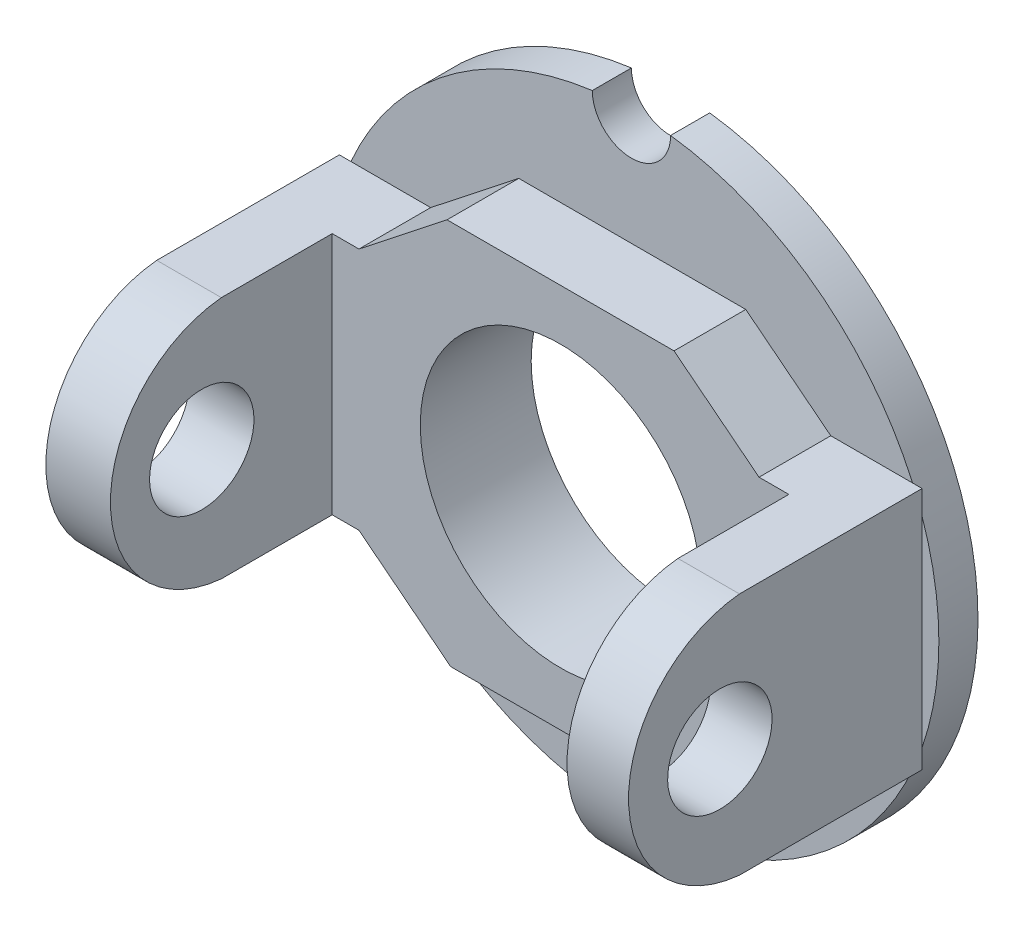
SolidWorks part; units mm, degrees
ref_plane "Plan de face" through (0, 0, 0) normal (0, 0, 1) x (1, 0, 0)
ref_plane "Plan de dessus" through (0, 0, 0) normal (0, 1, 0) x (1, 0, 0)
ref_plane "Plan de droite" through (0, 0, 0) normal (1, 0, 0) x (0, 0, -1)
sketch "Sketch1" plane through (0, 0, 0) normal (0, 0, 1) x (1, 0, 0)
  circle A0 centre (0, 0) radius 10.75
  arc A1 (2.9335, 23.3162) -> (-3.0665, 23.2991) centre (0, 0) cw
  arc A3 (-3.0665, 23.2991) -> (2.9335, 23.3162) centre (-0.0665, 23.3076) ccw
  point P5 (0.0671, -23.4999)
  point P6 (-0.0665, 23.5001)
  point P7 (0, 0)
  dimension "D1" = 21.5
  dimension "D3" = 23.5
  dimension "D4" = 3
  dimension "D2" = 47
  dimension "D5" = 6
extrude "Boss-Extrude1" add sketch "Sketch1" along normal blind 3
sketch "Sketch2" plane through (0, 0, 3) normal (0, 0, 1) x (1, 0, 0)
  line L0 (0, 0) -> (0, 14.6508) construction
  line L1 (-8.7, 14.6508) -> (8.7, 14.6508)
  line L7 (-15.4527, -9.335) -> (-15.4527, 9.335)
  line L8 (-15.4527, 9.335) -> (-8.7, 14.6508)
  line L9 (8.7, 14.6508) -> (15.2147, 9.5224)
  line L10 (15.2147, 9.5224) -> (15.2147, -9.1476)
  line L14 (-8.4225, -14.8692) -> (7.9465, -14.8692)
  line L15 (-8.4225, -14.8692) -> (-15.4527, -9.335)
  line L16 (15.2147, -9.1476) -> (7.9465, -14.8692)
  line L18 (15.2147, 9.5224) -> (22.2147, 9.5224)
  line L19 (15.2147, 9.5224) -> (15.2147, -9.1476)
  line L20 (15.2147, -9.1476) -> (22.2147, -9.1476)
  line L21 (22.2147, 9.5224) -> (22.2147, -9.1476)
  line L22 (-15.4527, 9.335) -> (-22.4527, 9.335)
  line L23 (-15.4527, 9.335) -> (-15.4527, -9.335)
  line L24 (-15.4527, -9.335) -> (-22.4527, -9.335)
  line L25 (-22.4527, 9.335) -> (-22.4527, -9.335)
  circle A0 centre (0, 0) radius 10.75
  point P12 (-15.4527, 0)
  point P13 (0, 14.6508)
  dimension "D1" = 18.67
  dimension "D2" = 141.79
  dimension "D3" = 17.4
  dimension "D4" = 141.79
  dimension "D5" = 18.67
  dimension "D6" = 29.52
  dimension "D7" = 141.79
  dimension "D8" = 141.79
  dimension "D9" = 7
  dimension "D10" = 7
extrude "Boss-Extrude2" add sketch "Sketch2" along normal blind 5.5
sketch "Sketch3" plane through (0, 0, 8.5) normal (0, 0, 1) x (1, 0, 0)
  line L0 (-15.4527, -9.335) -> (-22.4527, -9.335) construction
  line L1 (-22.4527, 9.335) -> (-17.5, 9.335)
  line L2 (-22.4527, 9.335) -> (-22.4527, -9.335)
  line L3 (-22.4527, -9.335) -> (-17.5, -9.335)
  line L4 (-17.5, 9.335) -> (-17.5, -9.335)
  line L5 (15.2147, -9.1476) -> (22.2147, -9.1476) construction
  line L6 (22.2147, 9.5224) -> (17.5, 9.5224)
  line L7 (22.2147, 9.5224) -> (22.2147, -9.1476)
  line L8 (22.2147, -9.1476) -> (17.5, -9.1476)
  line L9 (17.5, 9.5224) -> (17.5, -9.1476)
  dimension "D1" = 35
  dimension "D2" = 17.5
extrude "Boss-Extrude3" add sketch "Sketch3" along normal blind 17
sketch "Sketch4" plane through (-22.4527, 0, 0) normal (-1, 0, 0) x (0, 0, 1)
  line L0 (25.5, 9.335) -> (17, 9.335) construction
  line L1 (25.5, 9.335) -> (3, 9.335) construction
  line L2 (25.5, -9.335) -> (17, -9.335) construction
  line L4 (25.5, -9.335) -> (3, -9.335) construction
  line L5 (17, 9.335) -> (17, 13.6336)
  line L6 (17, 13.6336) -> (31.0273, 13.6336)
  line L7 (31.0273, 13.6336) -> (31.0273, -15.4296)
  line L8 (31.0273, -15.4296) -> (17, -15.4296)
  line L9 (17, -15.4296) -> (17, -9.335)
  arc A0 (17, 9.335) -> (17, -9.335) centre (16.124, 0) cw
  dimension "D1" = 8.5
  dimension "D2" = 8.5
extrude "Cut-Extrude1" cut sketch "Sketch4" against normal blind 17
sketch "Sketch5" plane through (-22.4527, 0, 0) normal (-1, 0, 0) x (0, 0, 1)
  circle A0 centre (18.5, 0.0017) radius 4
  arc A1 (17, -9.335) -> (17, 9.335) centre (16.124, 0) ccw construction
  point P5 (25.5, 0)
  dimension "D2" = 8
  dimension "D1" = 7
extrude "Cut-Extrude2" cut sketch "Sketch5" against normal blind 17
sketch "Sketch6" plane through (22.2147, 0, 0) normal (1, 0, 0) x (0, 0, -1)
  line L0 (-25.5, -9.1476) -> (-17, -9.1476) construction
  line L1 (-25.5, -9.1476) -> (-3, -9.1476) construction
  line L2 (-17, -9.1476) -> (-17, 9.5224) construction
  line L3 (-25.5, 9.5224) -> (-3, 9.5224) construction
  line L4 (-17, 9.5224) -> (-25.5, 9.5224) construction
  line L5 (-17, 9.5224) -> (-17, 12.0176)
  line L6 (-17, 12.0176) -> (-28.3232, 12.0176)
  line L7 (-28.3232, 12.0176) -> (-28.3232, -10.5543)
  line L8 (-28.3232, -10.5543) -> (-17, -10.5543)
  line L9 (-17, -10.5543) -> (-17, -9.1476)
  arc A0 (-17, -9.1476) -> (-17, 9.5224) centre (-16.124, 0.1874) cw
  dimension "D1" = 8.5
extrude "Cut-Extrude3" cut sketch "Sketch6" against normal blind 17
sketch "Sketch7" plane through (22.2147, 0, 0) normal (1, 0, 0) x (0, 0, -1)
  circle A0 centre (-18.5032, -0.0237) radius 4
  arc A1 (-17, 9.5224) -> (-17, -9.1476) centre (-16.124, 0.1874) ccw construction
  point P5 (-25.5, 0.1874)
  dimension "D2" = 8
  dimension "D1" = 7
extrude "Cut-Extrude4" cut sketch "Sketch7" against normal blind 17
